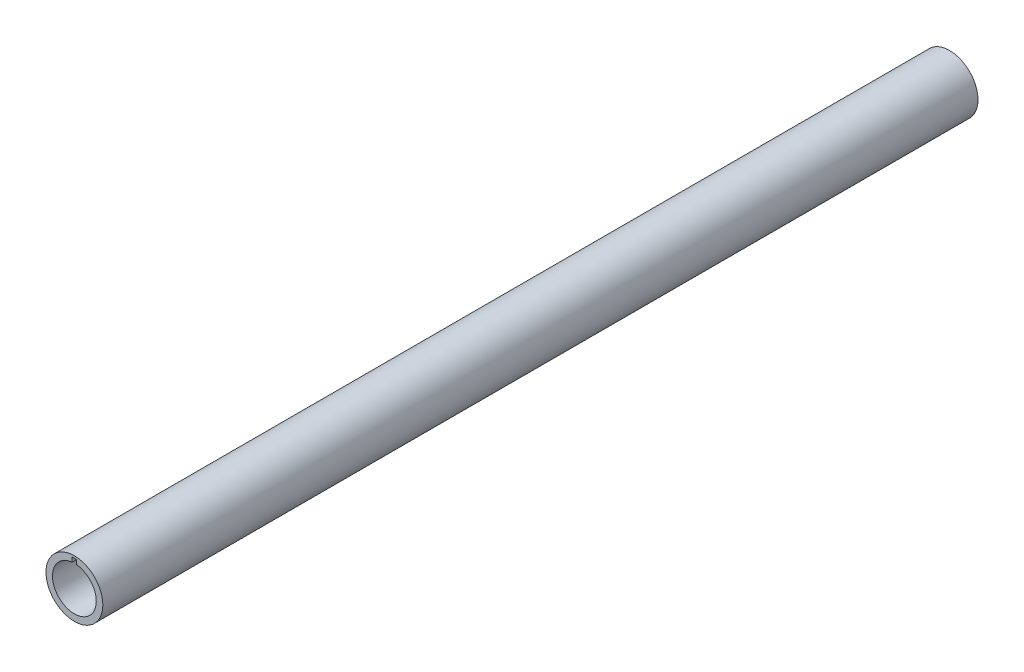
SolidWorks part; units mm, degrees
ref_plane "Front Plane" through (0, 0, 0) normal (0, 0, 1) x (1, 0, 0)
ref_plane "Top Plane" through (0, 0, 0) normal (0, 1, 0) x (1, 0, 0)
ref_plane "Right Plane" through (0, 0, 0) normal (1, 0, 0) x (0, 0, -1)
sketch "Sketch1" plane through (0, 0, 0) normal (0, 0, 1) x (1, 0, 0)
  circle A0 centre (0, 0) radius 10
  circle A1 centre (0, 0) radius 13
  dimension "D1" = 20
  dimension "D2" = 26
extrude "Boss-Extrude1" add sketch "Sketch1" along normal blind 400
sketch "Sketch2" plane through (0, 0, 400) normal (0, 0, 1) x (1, 0, 0)
  line L0 (0, 0) -> (0, 10) construction
  line L1 (0, 10) -> (-1, 10) construction
  line L4 (-1, 9.9499) -> (-1, 12)
  line L5 (-1, 12) -> (1, 12)
  line L6 (1, 9.9499) -> (1, 12)
  circle A0 centre (0, 0) radius 10 construction
  arc A1 (1, 9.9499) -> (-1, 9.9499) centre (0, 0) ccw
  dimension "D1" = 1
  dimension "D2" = 1
  dimension "D3" = 2
extrude "Cut-Extrude1" cut sketch "Sketch2" against normal blind 20
sketch "Sketch3" plane through (0, 0, 0) normal (0, 0, -1) x (-1, 0, 0)
  line L0 (0, 0) -> (0, 10) construction
  line L4 (-1, 9.9499) -> (-1, 11.9499)
  line L5 (-1, 11.9499) -> (1, 11.9499)
  line L6 (1, 9.9499) -> (1, 11.9499)
  circle A0 centre (0, 0) radius 10 construction
  arc A1 (1, 9.9499) -> (-1, 9.9499) centre (0, 0) ccw
  dimension "D1" = 2
  dimension "D2" = 2
  dimension "D3" = 1
extrude "Cut-Extrude2" cut sketch "Sketch3" against normal blind 20
